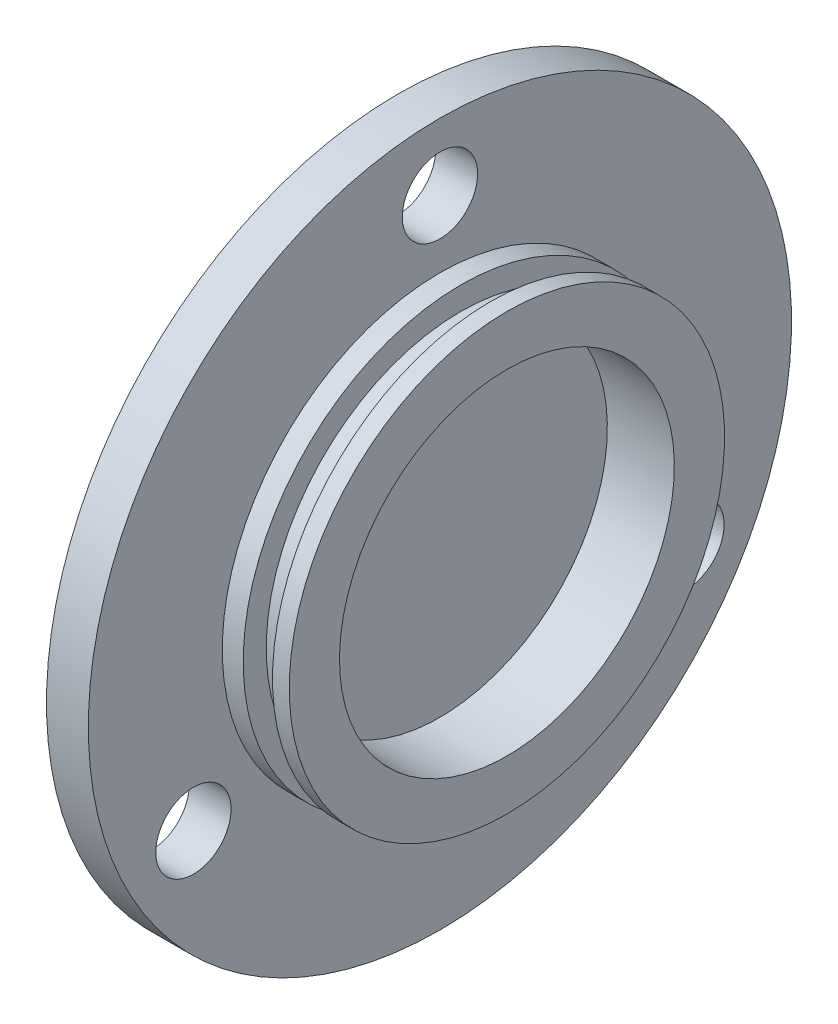
SolidWorks part; units mm, degrees
ref_plane "Piano frontale" through (0, 0, 0) normal (0, 0, 1) x (1, 0, 0)
ref_plane "Piano superiore" through (0, 0, 0) normal (0, 1, 0) x (1, 0, 0)
ref_plane "Piano destro" through (0, 0, 0) normal (1, 0, 0) x (0, 0, -1)
sketch "Schizzo1" plane through (0, 0, 0) normal (0, 0, 1) x (1, 0, 0)
  line L0 (0, 0) -> (0, 42)
  line L1 (0, 42) -> (5, 42)
  line L2 (5, 42) -> (5, 26)
  line L3 (5, 26) -> (7.5, 26)
  line L4 (13, 26) -> (13, 20)
  line L5 (13, 20) -> (5, 20)
  line L6 (5, 20) -> (5, 0)
  line L7 (5, 0) -> (0, 0)
  line L8 (7.5, 26) -> (7.5, 23.25)
  line L9 (7.5, 23.25) -> (11, 23.25)
  line L10 (11, 23.25) -> (11, 26)
  line L11 (11, 26) -> (13, 26)
  point P5 (13, 23)
  point P11 (2.5, 0)
  dimension "D1" = 5
  dimension "D2" = 26
  dimension "12" = 13
  dimension "D3" = 42
  dimension "D4" = 5
  dimension "D5" = 20
  dimension "D6" = 23.25
  dimension "D7" = 2
  dimension "2.5" = 3.5
revolve "Rivoluzione1" add sketch "Schizzo1" angle 360 about L7
sketch "Schizzo2" plane through (5, 0, 0) normal (1, 0, 0) x (0, 0, -1)
  circle A0 centre (0, 34) radius 4.5
  circle A1 centre (0, 0) radius 26 construction
  circle A2 centre (29.4449, -17) radius 4.5
  circle A3 centre (-29.4449, -17) radius 4.5
  point P11 (0, 0)
  dimension "D1" = 9
  dimension "D2" = 34
  dimension "D3" = 3
extrude "Taglio-Estrusione1" cut sketch "Schizzo2" against normal through all
